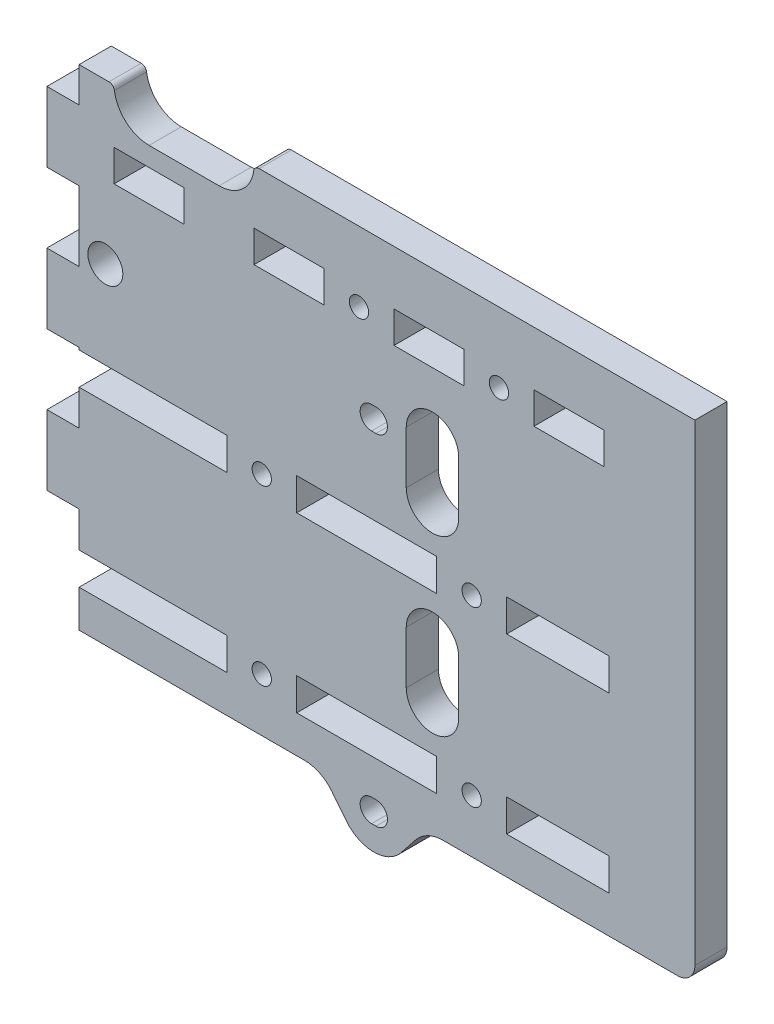
SolidWorks part; units mm, degrees
ref_plane "Front Plane" through (0, 0, 0) normal (0, 0, 1) x (1, 0, 0)
ref_plane "Top Plane" through (0, 0, 0) normal (0, 1, 0) x (1, 0, 0)
ref_plane "Right Plane" through (0, 0, 0) normal (1, 0, 0) x (0, 0, -1)
sketch "Sketch1" plane through (0, 0, 0) normal (0, 0, 1) x (1, 0, 0)
  line L0 (-61.722, 0) -> (-61.722, 12.7)
  line L1 (55.88, -44.45) -> (7.1279, -44.45)
  line L2 (55.88, -44.45) -> (55.88, 44.45)
  line L3 (55.88, 44.45) -> (-55.88, 44.45)
  line L4 (-55.88, -44.45) -> (-55.88, -37.692)
  line L5 (55.88, -44.45) -> (-55.88, 44.45) construction
  line L6 (55.88, 44.45) -> (-55.88, -44.45) construction
  line L7 (-61.722, 25.4) -> (-55.88, 25.4)
  line L8 (-61.722, 25.4) -> (-61.722, 38.1)
  line L9 (-61.722, 38.1) -> (-55.88, 38.1)
  line L10 (-55.88, 12.7) -> (-55.88, 25.4)
  line L11 (-61.722, 25.4) -> (-55.88, 38.1) construction
  line L12 (-61.722, 38.1) -> (-55.88, 25.4) construction
  line L13 (-61.722, 12.7) -> (-55.88, 12.7)
  line L14 (-61.722, 0) -> (-55.88, 0)
  line L15 (-61.722, -25.4) -> (-61.722, -12.7)
  line L16 (-61.722, -12.7) -> (-55.88, -12.7)
  line L17 (-61.722, -25.4) -> (-55.88, -25.4)
  line L18 (-61.722, 12.7) -> (-55.88, 0) construction
  line L19 (-61.722, 0) -> (-55.88, 12.7) construction
  line L20 (-61.722, -12.7) -> (-55.88, -25.4) construction
  line L21 (-61.722, -25.4) -> (-55.88, -12.7) construction
  line L22 (-55.88, 38.1) -> (-55.88, 44.45)
  line L23 (-55.88, -12.7) -> (-55.88, -6.25)
  line L24 (-55.88, -6.25) -> (55.88, -6.25) construction
  line L25 (-55.88, -31.85) -> (55.88, -31.85) construction
  line L26 (-58.801, -19.05) -> (-55.88, -19.05) construction
  line L27 (-55.88, -31.85) -> (-55.88, -6.25) construction
  line L28 (-55.88, -0.408) -> (-55.88, 0)
  line L29 (-29.083, -0.408) -> (-55.88, -0.408)
  line L30 (-29.083, -0.408) -> (-29.083, -6.25)
  line L31 (-29.083, -6.25) -> (-55.88, -6.25)
  line L32 (-58.801, -19.05) -> (55.88, -19.05) construction
  line L33 (-29.083, -0.408) -> (-55.88, -6.25) construction
  line L34 (-29.083, -6.25) -> (-55.88, -0.408) construction
  line L35 (9.017, -0.408) -> (-10.541, -0.408)
  line L36 (9.017, -0.408) -> (9.017, -6.25)
  line L37 (9.017, -6.25) -> (-10.541, -6.25)
  line L38 (27.559, -0.408) -> (21.717, -0.408)
  line L39 (9.017, -0.408) -> (-10.541, -6.25) construction
  line L40 (9.017, -6.25) -> (-10.541, -0.408) construction
  line L41 (40.259, -0.408) -> (27.559, -0.408)
  line L42 (40.259, -0.408) -> (40.259, -6.25)
  line L43 (40.259, -6.25) -> (27.559, -6.25)
  line L44 (-29.083, -37.692) -> (-55.88, -31.85) construction
  line L45 (40.259, -0.408) -> (27.559, -6.25) construction
  line L46 (40.259, -6.25) -> (27.559, -0.408) construction
  line L47 (-10.541, -0.408) -> (-16.383, -0.408)
  line L48 (-29.083, -31.85) -> (-55.88, -37.692) construction
  line L49 (-10.541, -6.25) -> (-16.383, -6.25)
  line L50 (-16.383, -0.408) -> (-16.383, -6.25)
  line L51 (27.559, -6.25) -> (21.717, -6.25)
  line L52 (21.717, -0.408) -> (21.717, -6.25)
  line L53 (-29.083, -31.85) -> (-55.88, -31.85)
  line L54 (-29.083, -37.692) -> (-55.88, -37.692)
  line L55 (40.259, -31.85) -> (27.559, -37.692) construction
  line L56 (40.259, -37.692) -> (27.559, -31.85) construction
  line L57 (9.017, -31.85) -> (-10.541, -37.692) construction
  line L58 (9.017, -37.692) -> (-10.541, -31.85) construction
  line L59 (21.717, -37.692) -> (21.717, -31.85)
  line L60 (27.559, -31.85) -> (21.717, -31.85)
  line L61 (-16.383, -37.692) -> (-16.383, -31.85)
  line L62 (-10.541, -31.85) -> (-16.383, -31.85)
  line L63 (-10.541, -37.692) -> (-16.383, -37.692)
  line L64 (40.259, -31.85) -> (27.559, -31.85)
  line L65 (40.259, -37.692) -> (40.259, -31.85)
  line L66 (40.259, -37.692) -> (27.559, -37.692)
  line L67 (27.559, -37.692) -> (21.717, -37.692)
  line L68 (9.017, -31.85) -> (-10.541, -31.85)
  line L69 (9.017, -37.692) -> (9.017, -31.85)
  line L70 (9.017, -37.692) -> (-10.541, -37.692)
  line L71 (-29.083, -37.692) -> (-29.083, -31.85)
  line L72 (-55.88, -31.85) -> (-55.88, -25.4)
  line L73 (-29.083, -3.329) -> (-16.383, -3.329) construction
  line L74 (21.717, -3.329) -> (9.017, -3.329) construction
  line L75 (21.717, -34.771) -> (9.017, -34.771) construction
  line L76 (-29.083, -34.771) -> (-16.383, -34.771) construction
  line L77 (-2.794, -46.228) -> (-2.0002, -46.228) construction
  line L78 (-2.794, -44.1452) -> (-2.0002, -44.1452)
  line L79 (-2.794, -48.3108) -> (-2.0002, -48.3108)
  line L80 (-11.9221, -44.45) -> (-55.88, -44.45)
  line L81 (-11.9221, -44.45) -> (-7.368, -50.1793)
  line L82 (7.1279, -44.45) -> (2.5738, -50.1793)
  line L83 (-2.794, 15.494) -> (-2.0002, 15.494) construction
  line L84 (-2.794, 17.5768) -> (-2.0002, 17.5768)
  line L85 (-2.794, 13.4112) -> (-2.0002, 13.4112)
  line L86 (-55.88, 31.75) -> (-11.43, 31.75) construction
  line L87 (-11.43, 28.879) -> (-11.43, 34.621)
  line L88 (-36.83, 28.879) -> (-49.53, 28.879)
  line L89 (-36.83, 28.879) -> (-36.83, 34.621)
  line L90 (-36.83, 34.621) -> (-49.53, 34.621)
  line L91 (-49.53, 28.879) -> (-49.53, 34.621)
  line L92 (-36.83, 28.879) -> (-49.53, 34.621) construction
  line L93 (-36.83, 34.621) -> (-49.53, 28.879) construction
  line L94 (-11.43, 28.879) -> (-24.13, 28.879)
  line L95 (-11.43, 34.621) -> (-24.13, 28.879) construction
  line L96 (-11.43, 28.879) -> (-24.13, 34.621) construction
  line L97 (-24.13, 28.879) -> (-24.13, 34.621)
  line L98 (-11.43, 34.621) -> (-24.13, 34.621)
  line L99 (13.97, 28.879) -> (13.97, 34.621)
  line L100 (13.97, 28.879) -> (1.27, 28.879)
  line L101 (13.97, 34.621) -> (1.27, 28.879) construction
  line L102 (13.97, 28.879) -> (1.27, 34.621) construction
  line L103 (1.27, 28.879) -> (1.27, 34.621)
  line L104 (13.97, 34.621) -> (1.27, 34.621)
  line L105 (39.37, 28.879) -> (39.37, 34.621)
  line L106 (39.37, 28.879) -> (26.67, 28.879)
  line L107 (39.37, 34.621) -> (26.67, 28.879) construction
  line L108 (39.37, 28.879) -> (26.67, 34.621) construction
  line L109 (26.67, 28.879) -> (26.67, 34.621)
  line L110 (39.37, 34.621) -> (26.67, 34.621)
  line L111 (26.67, 31.75) -> (55.88, 31.75) construction
  line L112 (1.27, 31.75) -> (13.97, 31.75) construction
  line L113 (-11.43, 31.75) -> (1.27, 31.75) construction
  line L114 (13.97, 31.75) -> (26.67, 31.75) construction
  circle A0 centre (-22.733, -3.329) radius 1.7526
  circle A1 centre (15.367, -3.329) radius 1.7526
  circle A2 centre (15.367, -34.771) radius 1.7526
  circle A3 centre (-22.733, -34.771) radius 1.7526
  arc A4 (-7.368, -50.1793) -> (2.5738, -50.1793) centre (-2.3971, -46.228) ccw
  arc A5 (-2.794, -44.1452) -> (-2.794, -48.3108) centre (-2.794, -46.228) ccw
  arc A6 (-2.0002, -48.3108) -> (-2.0002, -44.1452) centre (-2.0002, -46.228) ccw
  arc A7 (-2.794, 17.5768) -> (-2.794, 13.4112) centre (-2.794, 15.494) ccw
  arc A8 (-2.0002, 13.4112) -> (-2.0002, 17.5768) centre (-2.0002, 15.494) ccw
  circle A9 centre (-5.08, 31.75) radius 1.7526
  circle A10 centre (20.32, 31.75) radius 1.7526
  point P0 (0, 0)
  point P6 (-58.801, 31.75)
  point P20 (-58.801, 6.35)
  point P28 (-58.801, -19.05)
  point P35 (-42.4815, -3.329)
  point P36 (-0.762, -3.329)
  point P44 (33.909, -3.329)
  point P69 (33.909, -34.771)
  point P70 (-0.762, -34.771)
  point P71 (-42.4815, -34.771)
  point P72 (0, -38.1)
  point P93 (-2.3971, -46.228)
  point P104 (-2.3971, 15.494)
  point P110 (-43.18, 31.75)
  dimension "D14" = 3.5052
  dimension "D18" = 2.0828
  dimension "D22" = 12.7
  dimension "D31" = 3.5052
  dimension "D32" = 3.5052
  dimension "D1" = 12.7
  dimension "D2" = 5.842
  dimension "D3" = 12.7
  dimension "D6" = 25.4
  dimension "D7" = 111.76
  dimension "D8" = 25.6
  dimension "D9" = 5.842
  dimension "D10" = 26.797
  dimension "D11" = 5.842
  dimension "D12" = 5.842
  dimension "D13" = 19.558
  dimension "D15" = 12.7
  dimension "D16" = 5.842
  dimension "D19" = 90.678
  dimension "D20" = 53.086
  dimension "D21" = 0.7937
  dimension "D23" = 9.525
  dimension "D24" = 9.525
  dimension "D26" = 12.7
  dimension "D27" = 12.7
  dimension "D28" = 5.742
  dimension "D29" = 12.7
  dimension "D4" = 3
  dimension "D5" = 3
  dimension "D17" = 2
  dimension "D25" = 2
  dimension "D30" = 4
extrude "Boss-Extrude1" add sketch "Sketch1" along normal blind 5.842
sketch "Sketch2" plane through (0, 0, 5.842) normal (0, 0, 1) x (1, 0, 0)
  line L0 (55.88, 44.45) -> (-55.88, 44.45) construction
  line L1 (-55.88, 25.4) -> (-55.88, 12.7) construction
  circle A0 centre (-51.1175, 15.494) radius 3.175
  dimension "D1" = 6.35
  dimension "D2" = 28.956
  dimension "D3" = 4.7625
extrude "Cut-Extrude1" cut sketch "Sketch2" against normal through all
fillet "Fillet1" radius 6.35 2 edges at (7.1279, -44.45, 2.921) (-11.9221, -44.45, 2.921)
sketch "Sketch4" plane through (0, 0, 5.842) normal (0, 0, 1) x (1, 0, 0)
  line L0 (-43.18, 44.45) -> (-30.48, 44.45) construction
  line L1 (55.88, 44.45) -> (-55.88, 44.45) construction
  line L2 (-43.18, 50.8) -> (-30.48, 50.8)
  line L3 (-43.18, 38.1) -> (-30.48, 38.1)
  line L4 (-55.88, 44.45) -> (-55.88, 38.1) construction
  arc A0 (-43.18, 50.8) -> (-43.18, 38.1) centre (-43.18, 44.45) ccw
  arc A1 (-30.48, 38.1) -> (-30.48, 50.8) centre (-30.48, 44.45) ccw
  point P4 (-36.83, 44.45)
  dimension "D2" = 6.35
  dimension "D1" = 12.7
  dimension "D3" = 19.05
extrude "Cut-Extrude2" cut sketch "Sketch4" against normal through all
fillet "Fillet2" radius 1 2 edges at (-24.13, 44.45, 2.921) (-49.53, 44.45, 2.921)
fillet "Fillet3" radius 3.175 1 edges at (55.88, -44.45, 2.921)
sketch "Sketch5" plane through (0, 0, 5.842) normal (0, 0, 1) x (1, 0, 0)
  line L0 (-61.722, -19.05) -> (55.88, -19.05) construction
  line L1 (8.255, -23.8125) -> (8.255, -14.2875) construction
  line L2 (3.4925, -23.8125) -> (3.4925, -14.2875)
  line L3 (13.0175, -23.8125) -> (13.0175, -14.2875)
  line L4 (-61.722, -12.7) -> (-61.722, -25.4) construction
  line L5 (55.88, -41.275) -> (55.88, 44.45) construction
  line L6 (9.017, -3.329) -> (15.367, -3.329) construction
  line L7 (9.017, -6.25) -> (9.017, -0.408) construction
  line L8 (-61.722, 12.392) -> (55.88, 12.392) construction
  line L9 (8.255, 17.1545) -> (8.255, 7.6295) construction
  line L10 (3.4925, 17.1545) -> (3.4925, 7.6295)
  line L11 (13.0175, 17.1545) -> (13.0175, 7.6295)
  arc A0 (3.4925, -23.8125) -> (13.0175, -23.8125) centre (8.255, -23.8125) ccw
  arc A1 (13.0175, -14.2875) -> (3.4925, -14.2875) centre (8.255, -14.2875) ccw
  arc A2 (3.4925, 17.1545) -> (13.0175, 17.1545) centre (8.255, 17.1545) cw
  arc A3 (13.0175, 7.6295) -> (3.4925, 7.6295) centre (8.255, 7.6295) cw
  point P6 (8.255, -19.05)
  point P24 (8.255, 12.392)
  dimension "D2" = 4.7625
  dimension "D1" = 9.525
  dimension "D3" = 47.625
extrude "Cut-Extrude3" cut sketch "Sketch5" against normal through all
